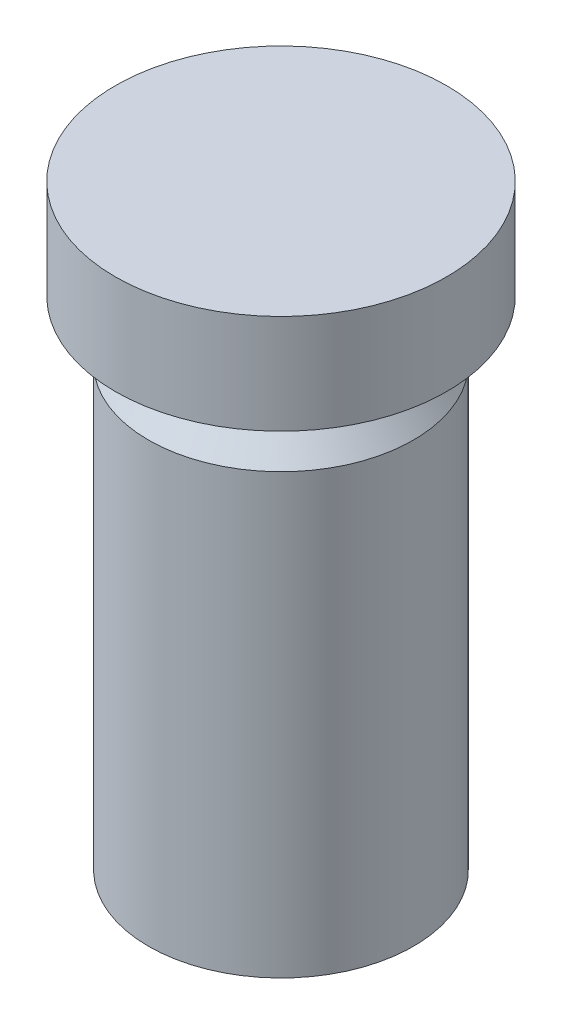
SolidWorks part; units mm, degrees
material "6061 Alloy"
ref_plane "Front Plane" through (0, 0, 0) normal (0, 0, 1) x (1, 0, 0)
ref_plane "Top Plane" through (0, 0, 0) normal (0, 1, 0) x (1, 0, 0)
ref_plane "Right Plane" through (0, 0, 0) normal (1, 0, 0) x (0, 0, -1)
sketch "Sketch2" plane through (0, 0, 0) normal (0, 0, 1) x (1, 0, 0)
  line L0 (2.0409, 44.45) -> (0, 42.0178)
  line L1 (0, 0) -> (2.2225, 0)
  line L2 (0, 0) -> (0, 42.0178)
  line L3 (2.0409, 44.45) -> (9.525, 44.45)
  line L6 (2.2225, 0) -> (2.2225, 12.7)
  line L7 (2.2225, 12.7) -> (12.7, 12.7)
  line L9 (12.7, 12.7) -> (12.7, 57.15)
  line L10 (9.525, 44.45) -> (9.525, 47.625)
  line L13 (-3.175, 47.625) -> (9.525, 47.625)
  line L14 (-3.175, 47.625) -> (-3.175, 57.15)
  line L15 (-3.175, 57.15) -> (12.7, 57.15)
  dimension "D1" = 12.7
  dimension "D2" = 44.45
  dimension "D3" = 2.2225
  dimension "D4" = 9.525
  dimension "D5" = 12.7
  dimension "D6" = 15.875
  dimension "D7" = 9.525
  dimension "D8" = 3.175
  dimension "D9" = 130
  dimension "D10" = 3.175
revolve "Revolve1" add sketch "Sketch2" angle 360 about L9
sketch "Sketch3" plane through (0, 0, 0) normal (0, 0, 1) x (1, 0, 0)
  line L0 (12.7, 0) -> (12.7, 57.15) construction
  line L3 (0, 0) -> (25.4, 0) construction
  line L4 (28.575, 57.15) -> (-3.175, 57.15) construction
  line L5 (25.4, 44.45) -> (0, 44.45) construction
  circle A0 centre (12.7, 25.4) radius 4.7625
  dimension "D1" = 19.05
  dimension "D2" = 9.525
extrude "Cut-Extrude1" cut sketch "Sketch3" against normal through all
